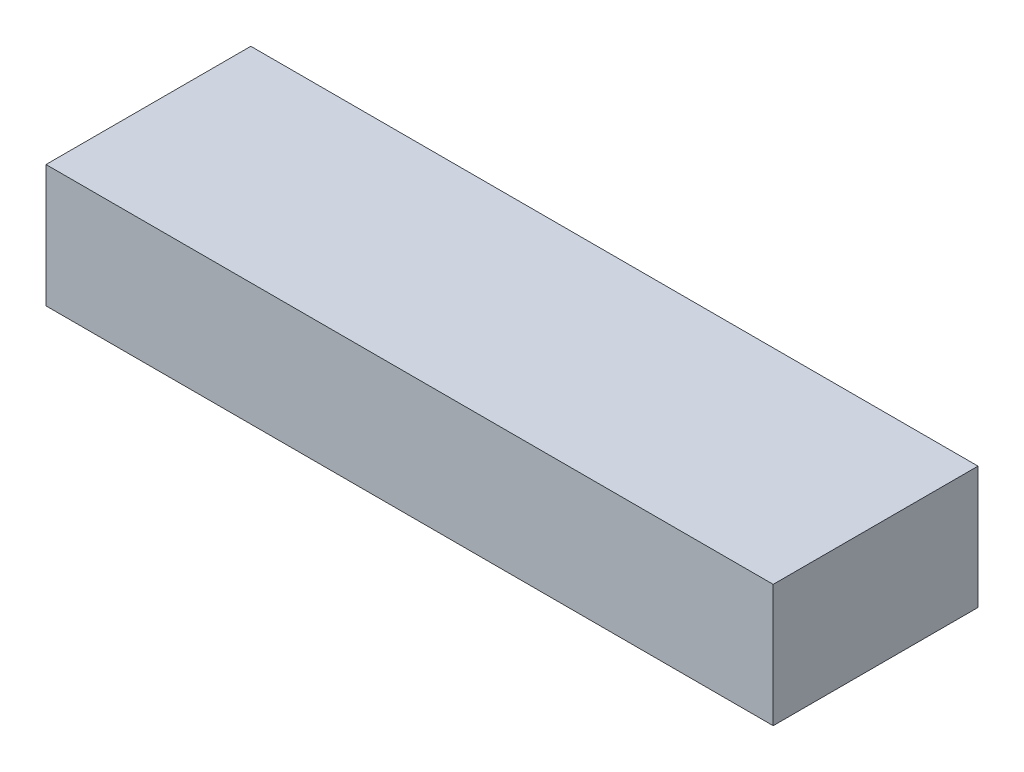
SolidWorks part; units mm, degrees
ref_plane "Front Plane" through (0, 0, 0) normal (0, 0, 1) x (1, 0, 0)
ref_plane "Top Plane" through (0, 0, 0) normal (0, 1, 0) x (1, 0, 0)
ref_plane "Right Plane" through (0, 0, 0) normal (1, 0, 0) x (0, 0, -1)
sketch "Sketch1" plane through (0, 0, 0) normal (0, 1, 0) x (1, 0, 0)
  line L1 (-62.9907, 38.25) -> (-3.6014, 38.25)
  line L2 (-62.9907, 38.25) -> (-62.9907, 21.5228)
  line L3 (-62.9907, 21.5228) -> (-3.6014, 21.5228)
  line L4 (-3.6014, 38.25) -> (-3.6014, 21.5228)
  point P4 (-14.3361, 21.1375)
  point P5 (-3.6014, 21.5228)
extrude "Boss-Extrude1" add sketch "Sketch1" along normal blind 10
sketch "Sketch2" plane through (0, 10, 0) normal (0, 1, 0) x (1, 0, 0)
  line L0 (-52.6678, 30.7086) -> (-50.1678, 30.7086) construction
  line L1 (-52.6678, 30.7086) -> (-52.6678, 28.2086) construction
  line L2 (-52.6678, 28.2086) -> (-52.6678, 25.7086) construction
  line L3 (-52.6678, 30.7086) -> (-46.6678, 30.7086) construction
  line L4 (-46.6678, 30.7086) -> (-46.6678, 22.9876) construction
  line L5 (-40.6678, 28.2086) -> (-40.6678, 25.7086) construction
  line L6 (-40.6678, 30.7086) -> (-40.6678, 28.2086) construction
  line L7 (-40.6678, 30.7086) -> (-43.1678, 30.7086) construction
  line L8 (-43.1678, 30.7086) -> (-37.1678, 30.7086) construction
  line L9 (-37.1678, 30.7086) -> (-37.1678, 24.2369) construction
  line L10 (-24.1678, 30.7086) -> (-18.1678, 30.7086) construction
  line L11 (-18.1678, 30.7086) -> (-18.1678, 22.4956) construction
  circle A0 centre (-52.6678, 30.7086) radius 1
  circle A1 centre (-50.1678, 30.7086) radius 1
  circle A2 centre (-52.6678, 28.2086) radius 1
  circle A3 centre (-50.1678, 28.2086) radius 1
  circle A4 centre (-52.6678, 25.7086) radius 1
  circle A5 centre (-50.1678, 25.7086) radius 1
  circle A6 centre (-43.1678, 25.7086) radius 1
  circle A7 centre (-40.6678, 25.7086) radius 1
  circle A8 centre (-43.1678, 28.2086) radius 1
  circle A9 centre (-40.6678, 28.2086) radius 1
  circle A10 centre (-43.1678, 30.7086) radius 1
  circle A11 centre (-40.6678, 30.7086) radius 1
  circle A12 centre (-33.6678, 25.7086) radius 1
  circle A13 centre (-31.1678, 25.7086) radius 1
  circle A14 centre (-33.6678, 28.2086) radius 1
  circle A15 centre (-33.6678, 30.7086) radius 1
  circle A16 centre (-31.1678, 28.2086) radius 1
  circle A17 centre (-31.1678, 30.7086) radius 1
  circle A18 centre (-24.1678, 25.7086) radius 1
  circle A19 centre (-21.6678, 25.7086) radius 1
  circle A20 centre (-24.1678, 28.2086) radius 1
  circle A21 centre (-21.6678, 28.2086) radius 1
  circle A22 centre (-24.1678, 30.7086) radius 1
  circle A23 centre (-21.6678, 30.7086) radius 1
  circle A24 centre (-14.6678, 25.7086) radius 1
  circle A25 centre (-12.1678, 25.7086) radius 1
  circle A26 centre (-14.6678, 28.2086) radius 1
  circle A27 centre (-14.6678, 30.7086) radius 1
  circle A28 centre (-12.1678, 28.2086) radius 1
  circle A29 centre (-12.1678, 30.7086) radius 1
  dimension "D2" = 2
  dimension "D1" = 2.5
  dimension "D3" = 2.5
  dimension "D4" = 6
